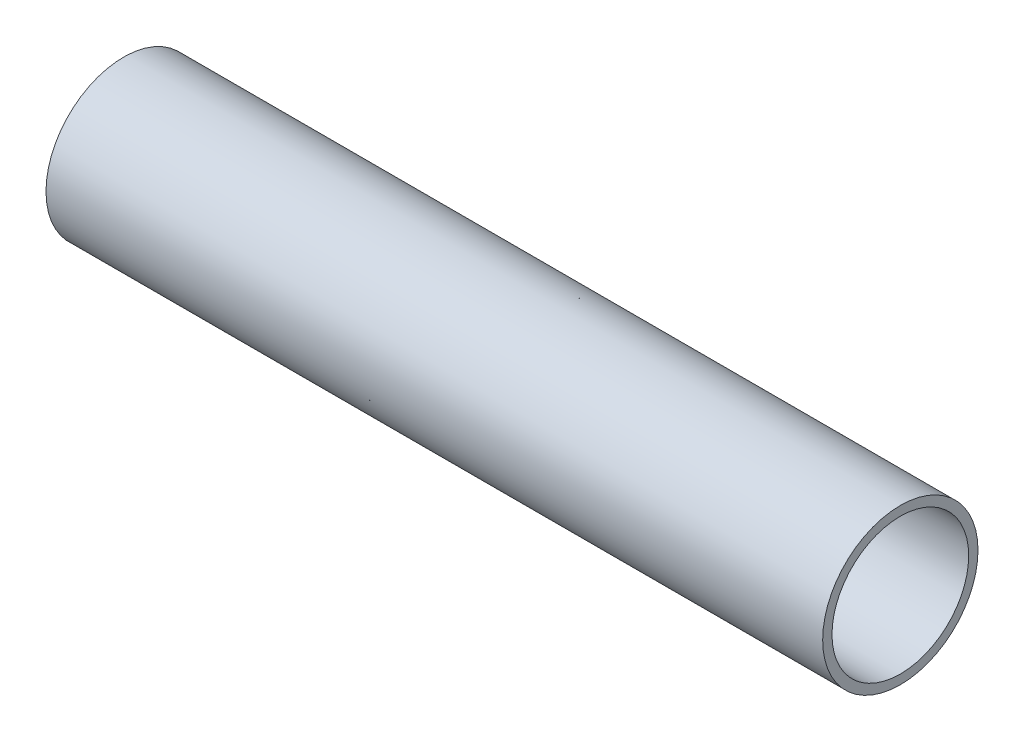
SolidWorks part; units mm, degrees
ref_plane "Спереди" through (0, 0, 0) normal (0, 0, 1) x (1, 0, 0)
ref_plane "Сверху" through (0, 0, 0) normal (0, 1, 0) x (1, 0, 0)
ref_plane "Справа" through (0, 0, 0) normal (1, 0, 0) x (0, 0, -1)
sketch "Эскиз1" plane through (0, 0, 0) normal (1, 0, 0) x (0, 0, -1)
  circle A0 centre (0, 0) radius 25
  circle A1 centre (0, 0) radius 22
  dimension "D1" = 50
  dimension "D2" = 3
extrude "Бобышка-Вытянуть1" add sketch "Эскиз1" along normal blind 125
sketch "Эскиз4" plane through (0, 0, 0) normal (-1, 0, 0) x (0, 0, 1)
  circle A0 centre (0, 0) radius 22 construction
  circle A1 centre (0, 0) radius 25
  circle A2 centre (0, 0) radius 25
  circle A3 centre (0, 0) radius 22
  dimension "D1" = 0
extrude "Бобышка-Вытянуть2" add sketch "Эскиз4" along normal blind 125
ref_point "Точка1"
